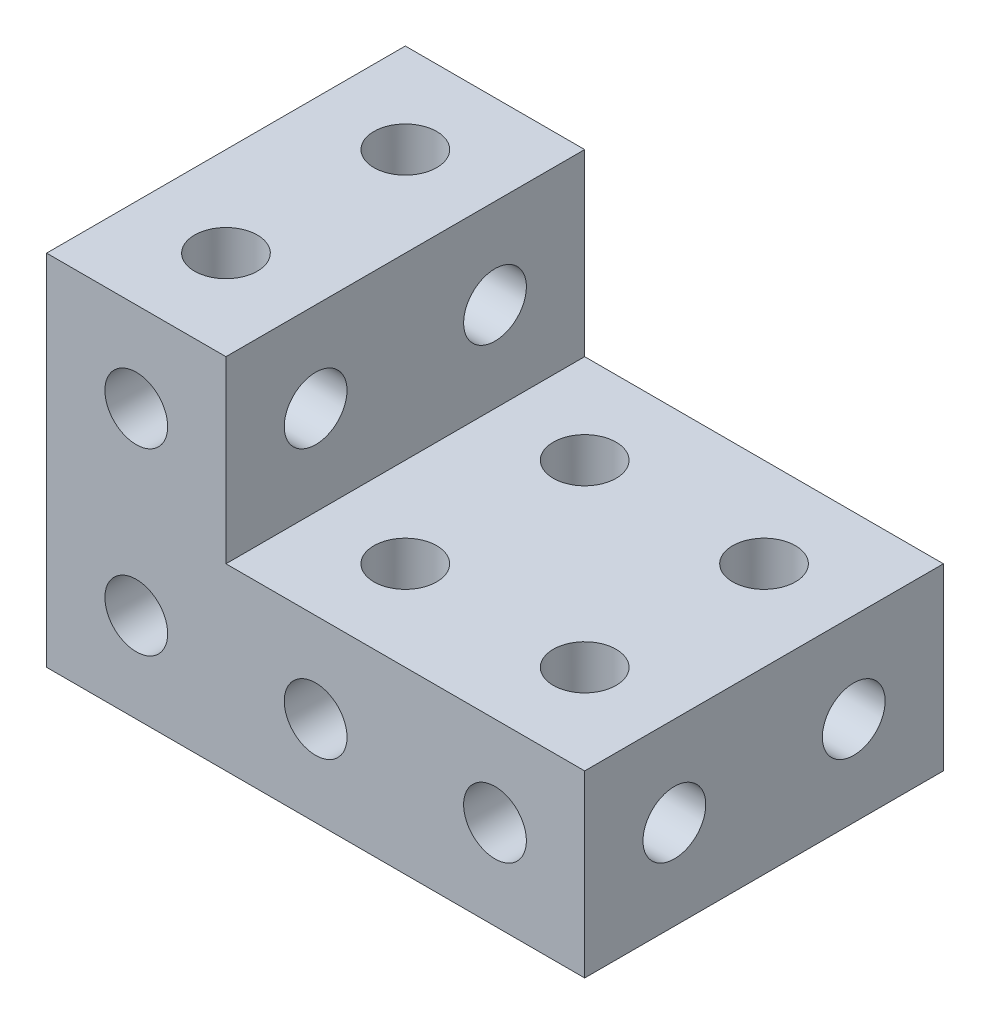
SolidWorks part; units mm, degrees
ref_plane "Plan de face" through (0, 0, 0) normal (0, 0, 1) x (1, 0, 0)
ref_plane "Plan de dessus" through (0, 0, 0) normal (0, 1, 0) x (1, 0, 0)
ref_plane "Plan de droite" through (0, 0, 0) normal (1, 0, 0) x (0, 0, -1)
sketch "Esquisse1" plane through (0, 0, 0) normal (0, 0, 1) x (1, 0, 0)
  line L0 (0, 0) -> (30, 0)
  line L1 (30, 0) -> (30, 10)
  line L2 (30, 10) -> (10, 10)
  line L3 (10, 10) -> (10, 20)
  line L4 (10, 20) -> (0, 20)
  line L5 (0, 20) -> (0, 0)
  dimension "D1" = 10
  dimension "D2" = 20
  dimension "D3" = 10
  dimension "D4" = 20
extrude "Boss.-Extru.1" add sketch "Esquisse1" along normal blind 20
sketch "Esquisse2" plane through (0, 0, 0) normal (0, -1, 0) x (1, 0, 0)
  line L0 (0, 15) -> (30, 15) construction
  line L1 (0, 20) -> (0, 0) construction
  line L2 (30, 20) -> (30, 0) construction
  line L3 (0, 20) -> (30, 20) construction
  circle A0 centre (5, 15) radius 1.75
  circle A1 centre (15, 15) radius 1.75
  circle A2 centre (25, 15) radius 1.75
  circle A3 centre (15, 5) radius 1.75
  circle A4 centre (25, 5) radius 1.75
  circle A5 centre (5, 5) radius 1.75
  dimension "D1" = 3.5
  dimension "D2" = 5
  dimension "D3" = 5
  dimension "D4" = 3
  dimension "D5" = 2
extrude "Enlèv. mat.-Extru.1" cut sketch "Esquisse2" against normal through all
sketch "Esquisse3" plane through (0, 0, 0) normal (-1, 0, 0) x (0, 0, 1)
  line L0 (20, 5) -> (-0.0357, 5) construction
  line L1 (20, 20) -> (20, 0) construction
  line L2 (20, 0) -> (0, 0) construction
  circle A0 centre (15, 5) radius 1.75
  circle A1 centre (5, 5) radius 1.75
  circle A2 centre (5, 15) radius 1.75
  circle A3 centre (15, 15) radius 1.75
  dimension "D1" = 3.5
  dimension "D2" = 5
  dimension "D3" = 5
  dimension "D4" = 2
  dimension "D5" = 2
extrude "Enlèv. mat.-Extru.2" cut sketch "Esquisse3" against normal through all
sketch "Esquisse4" plane through (0, 0, 20) normal (0, 0, 1) x (1, 0, 0)
  line L0 (30, 5) -> (0, 5) construction
  line L1 (30, 0) -> (30, 10) construction
  line L2 (0, 20) -> (0, 0) construction
  circle A0 centre (25, 5) radius 1.75
  circle A1 centre (15, 5) radius 1.75
  circle A2 centre (5, 5) radius 1.75
  circle A3 centre (15, 15) radius 1.75
  circle A4 centre (5, 15) radius 1.75
  circle A5 centre (25, 15) radius 1.75
  dimension "D1" = 3.5
  dimension "D2" = 5
  dimension "D3" = 3
  dimension "D4" = 2
extrude "Enlèv. mat.-Extru.3" cut sketch "Esquisse4" against normal blind 20
